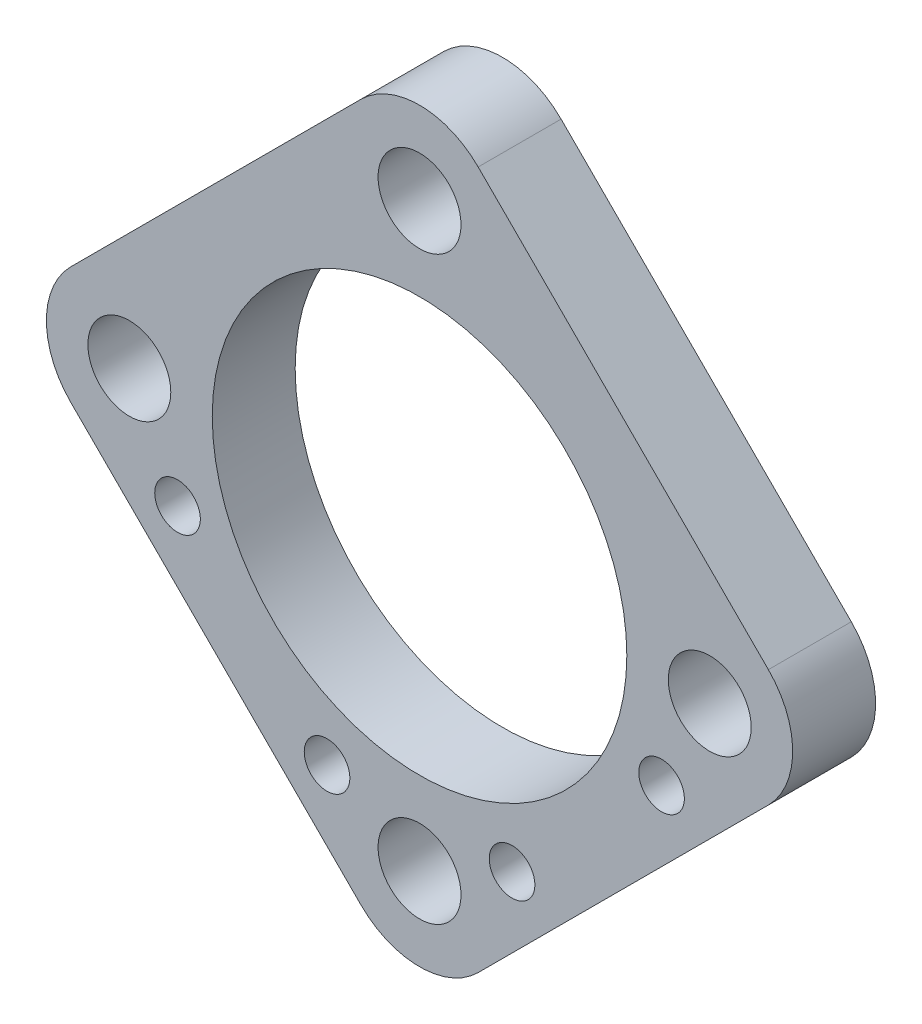
SolidWorks part; units mm, degrees
ref_plane "Płaszczyzna przednia" through (0, 0, 0) normal (0, 0, 1) x (1, 0, 0)
ref_plane "Płaszczyzna górna" through (0, 0, 0) normal (0, 1, 0) x (1, 0, 0)
ref_plane "Płaszczyzna prawa" through (0, 0, 0) normal (1, 0, 0) x (0, 0, -1)
sketch "Szkic1" plane through (0, 0, 0) normal (0, 0, 1) x (1, 0, 0)
  line L0 (-42.0711, 7.0711) -> (-7.0711, 42.0711)
  line L1 (7.0711, 42.0711) -> (42.0711, 7.0711)
  line L2 (-7.0711, -42.0711) -> (-42.0711, -7.0711)
  line L3 (42.0711, -7.0711) -> (7.0711, -42.0711)
  circle A1 centre (-35, 0) radius 5
  circle A2 centre (0, 35) radius 5
  circle A3 centre (35, 0) radius 5
  circle A4 centre (0, -35) radius 5
  circle A5 centre (0, 0) radius 25
  arc A7 (-42.0711, 7.0711) -> (-42.0711, -7.0711) centre (-35, 0) ccw
  arc A9 (42.0711, -7.0711) -> (42.0711, 7.0711) centre (35, 0) ccw
  arc A10 (-7.0711, -42.0711) -> (7.0711, -42.0711) centre (0, -35) ccw
  arc A12 (7.0711, 42.0711) -> (-7.0711, 42.0711) centre (0, 35) ccw
  dimension "D1" = 35
  dimension "D2" = 10
  dimension "D3" = 10
  dimension "D4" = 10
  dimension "D5" = 10
  dimension "D6" = 50
  dimension "D7" = 10
  dimension "D10" = 10
  dimension "D8" = 70
  dimension "D9" = 70
extrude "Dodanie-wyciągnięcie1" add sketch "Szkic1" along normal blind 10
sketch "Szkic2" plane through (0, 0, 0) normal (0, 0, -1) x (-1, 0, 0)
  line L0 (29.1881, -11.4688) -> (11.1569, -29.5)
  line L1 (-11.1569, -29.5) -> (-29.1881, -11.4688)
  line L2 (-42.0711, -7.0711) -> (-7.0711, -42.0711) construction
  line L3 (7.0711, -42.0711) -> (42.0711, -7.0711) construction
  line L4 (11.1569, -29.5) -> (-11.1569, -29.5)
  line L5 (29.1881, -11.4688) -> (-29.1881, -11.4688)
  circle A0 centre (11.1569, -29.5) radius 2.75
  circle A1 centre (29.1881, -11.4688) radius 2.75
  circle A2 centre (-11.1569, -29.5) radius 2.75
  circle A3 centre (-29.1881, -11.4688) radius 2.75
  circle A4 centre (35, 0) radius 5 construction
  circle A5 centre (0, -35) radius 5 construction
  dimension "D1" = 5.5
  dimension "D3" = 4
  dimension "D5" = 4
  dimension "D4" = 5.5
  dimension "D2" = 25.5
extrude "Wytnij-wyciągnięcie1" cut sketch "Szkic2" against normal through all both and the other way through all contours A1 | A0 | A2 | A3
